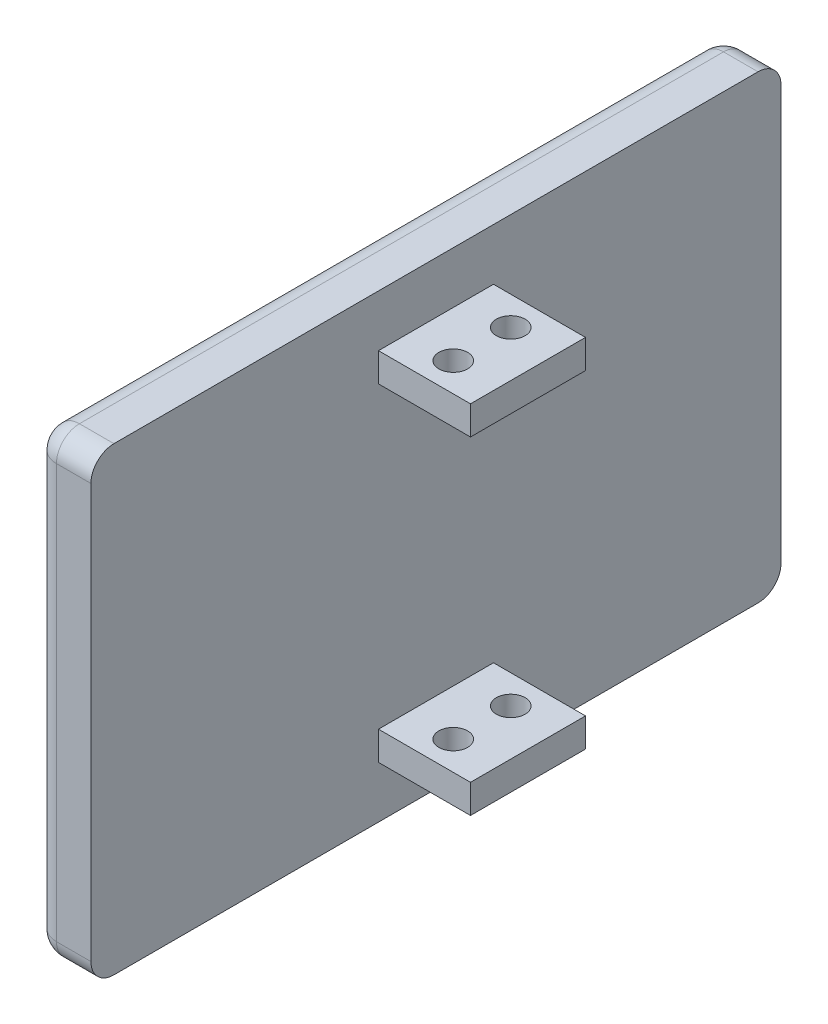
SolidWorks part; units mm, degrees
material "6061-T6 (SS)"
ref_plane "X-Y Datum" through (0, 0, 0) normal (0, 0, 1) x (1, 0, 0)
ref_plane "X-Z Datum" through (0, 0, 0) normal (0, 1, 0) x (1, 0, 0)
ref_plane "Y-Z Datum" through (0, 0, 0) normal (1, 0, 0) x (0, 0, -1)
sketch "Sketch1" plane through (0, 0, 0) normal (1, 0, 0) x (0, 0, -1)
  line L1 (38.1, -25.4) -> (-38.1, -25.4)
  line L2 (38.1, -25.4) -> (38.1, 25.4)
  line L3 (38.1, 25.4) -> (-38.1, 25.4)
  line L4 (-38.1, -25.4) -> (-38.1, 25.4)
  line L5 (38.1, -25.4) -> (-38.1, 25.4) construction
  line L6 (38.1, 25.4) -> (-38.1, -25.4) construction
  point P0 (0, 0)
  dimension "D1" = 50.8
  dimension "D2" = 76.2
extrude "Boss-Extrude1" add sketch "Sketch1" along normal blind 6.35
sketch "Sketch2" plane through (6.35, 0, 0) normal (1, 0, 0) x (0, 0, -1)
  line L0 (-38.1, 25.4) -> (-38.1, -25.4) construction
  line L1 (-6.35, -19.685) -> (6.35, -19.685)
  line L2 (-6.35, -19.685) -> (-6.35, -16.51)
  line L3 (-6.35, -16.51) -> (6.35, -16.51)
  line L4 (6.35, -19.685) -> (6.35, -16.51)
  line L5 (38.1, -25.4) -> (38.1, 25.4) construction
  line L6 (-38.1, 0) -> (38.1, 0) construction
  line L7 (-6.35, 16.51) -> (6.35, 16.51)
  line L8 (6.35, 19.685) -> (6.35, 16.51)
  line L9 (-6.35, 19.685) -> (6.35, 19.685)
  line L10 (-6.35, 19.685) -> (-6.35, 16.51)
  point P16 (0, -16.51)
  point P17 (0, 0)
  dimension "D1" = 3.175
  dimension "D2" = 16.51
  dimension "D3" = 12.7
extrude "Boss-Extrude2" add sketch "Sketch2" along normal blind 10.16
fillet "Fillet1" radius 2.54 8 edges at (3.175, 25.4, -38.1) (3.175, -25.4, -38.1) (3.175, -25.4, 38.1) (3.175, 25.4, 38.1) (0, -25.4, 0) (0, 0, -38.1) (0, 25.4, 0) (0, 0, 38.1)
sketch "Sketch3" plane through (0, 19.685, 0) normal (0, 1, 0) x (1, 0, 0)
  line L1 (6.35, 6.35) -> (6.35, -6.35) construction
  line L2 (11.43, -3.175) -> (11.43, 3.175) construction
  line L4 (11.43, 0) -> (16.51, 0) construction
  line L5 (16.51, 6.35) -> (16.51, -6.35) construction
  circle A0 centre (11.43, -3.175) radius 1.5875
  circle A1 centre (11.43, 3.175) radius 1.5875
  dimension "D1" = 3.175
  dimension "D3" = 5.08
  dimension "D2" = 6.35
extrude "Cut-Extrude1" cut sketch "Sketch3" against normal up to surface (39.37 mm away) up to face at (11.43, -19.685, 0)
